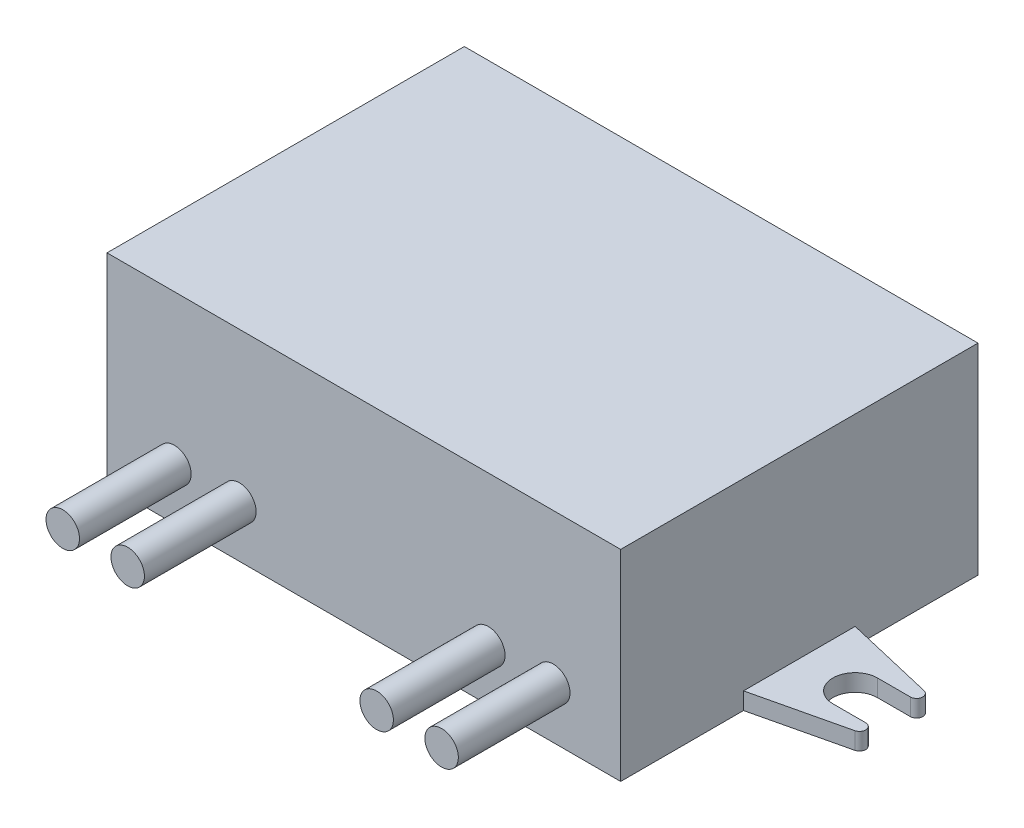
SolidWorks part; units mm, degrees
ref_plane "前视基准面" through (0, 0, 0) normal (0, 0, 1) x (1, 0, 0)
ref_plane "上视基准面" through (0, 0, 0) normal (0, 1, 0) x (1, 0, 0)
ref_plane "右视基准面" through (0, 0, 0) normal (1, 0, 0) x (0, 0, -1)
other "Configuration Table"
sketch "草图1" plane through (0, 0, 0) normal (0, 1, 0) x (1, 0, 0)
  line L1 (23, -16) -> (-23, -16)
  line L2 (23, -16) -> (23, 16)
  line L3 (23, 16) -> (-23, 16)
  line L4 (-23, -16) -> (-23, 16)
  line L5 (23, -16) -> (-23, 16) construction
  line L6 (23, 16) -> (-23, -16) construction
  point P0 (0, 0)
  dimension "D1" = 46
  dimension "D2" = 32
extrude "凸台-拉伸1" add sketch "草图1" along normal blind 18
sketch "草图2" plane through (0, 0, 16) normal (0, 0, 1) x (1, 0, 0)
  line L1 (31.5, 1.528) -> (-31.5, 1.528)
  line L2 (31.5, 1.528) -> (31.5, 0)
  line L3 (31.5, 0) -> (-31.5, 0)
  line L4 (-31.5, 1.528) -> (-31.5, 0)
  line L5 (31.5, 1.528) -> (-31.5, 0) construction
  line L6 (31.5, 0) -> (-31.5, 1.528) construction
  point P0 (0, 0.764)
  point P5 (0, 0)
  dimension "D1" = 63
extrude "凸台-拉伸2" add sketch "草图2" against normal through all
sketch "草图3" plane through (0, 1.528, 0) normal (0, 1, 0) x (1, 0, 0)
  line L0 (-23, 16) -> (-23, -16) construction
  line L1 (-28, 2) -> (-31.5, 2)
  line L2 (-31.5, 16) -> (-31.5, -16) construction
  line L3 (-28, -2) -> (-31.5, -2)
  line L4 (-31.5, 3) -> (-23, 5)
  line L5 (-31.5, -3) -> (-23, -5)
  line L6 (-23, 16) -> (-23, -16) construction
  line L7 (-31.5, 3) -> (-31.5, 2)
  line L8 (-31.5, -2) -> (-31.5, -3)
  line L9 (-23, 5) -> (-23, -5)
  line L10 (-23, 5) -> (-23, 16)
  line L11 (-23, 16) -> (-31.5, 16)
  line L12 (-31.5, 16) -> (-31.5, 3)
  line L13 (-31.5, -3) -> (-31.5, -16)
  line L14 (-31.5, -16) -> (-23, -16)
  line L15 (-23, -16) -> (-23, -5)
  arc A0 (-28, -2) -> (-28, 2) centre (-28, 0) ccw
  line M9 (-23, -16) -> (-23, 16)
  line M10 (-23, 16) -> (-31.5, 16)
  line M11 (-31.5, 16) -> (-31.5, -16)
  line M12 (-31.5, -16) -> (-23, -16)
  dimension "D1" = 28
  dimension "D4" = 4
  dimension "D2" = 1
  dimension "D3" = 1
  dimension "D5" = 2
  dimension "D6" = 2
extrude "切除-拉伸1" cut sketch "草图3" against normal through all contours L4 M11 M9 M10 | L5 M11 M12 M9 | L3 A0 L1 M11
fillet "圆角1" radius 0.558 4 edges at (-31.5, 1.528, -2.5) (-31.5, 0, -2.5) (-31.5, 0.764, -3) (-31.5, 0.764, -2)
fillet "圆角2" radius 0.558 4 edges at (-31.5, 1.528, 2.5) (-31.5, 0, 2.5) (-31.5, 0.764, 3) (-31.5, 0.764, 2)
mirror "镜向4" about plane through (0, 0, 0) normal (1, 0, 0) of "切除-拉伸1"
fillet "圆角3" radius 0.558 4 edges at (31.5, 1.528, -2.5) (31.5, 0, -2.5) (31.5, 0.764, -3) (31.5, 0.764, -2)
fillet "圆角4" radius 0.558 4 edges at (31.5, 1.528, 2.5) (31.5, 0, 2.5) (31.5, 0.764, 3) (31.5, 0.764, 2)
sketch "草图5" plane through (0, 0, 16) normal (0, 0, 1) x (1, 0, 0)
  line L0 (0, 0) -> (0, 18) construction
  line L1 (-23, 18) -> (23, 18) construction
  circle A0 centre (-16.9636, 4.5939) radius 1.5
  circle A1 centre (-11.1475, 4.5939) radius 1.5
  circle A2 centre (11.1475, 4.5939) radius 1.5
  circle A3 centre (16.9636, 4.5939) radius 1.5
extrude "凸台-拉伸3" add sketch "草图5" along normal blind 10
